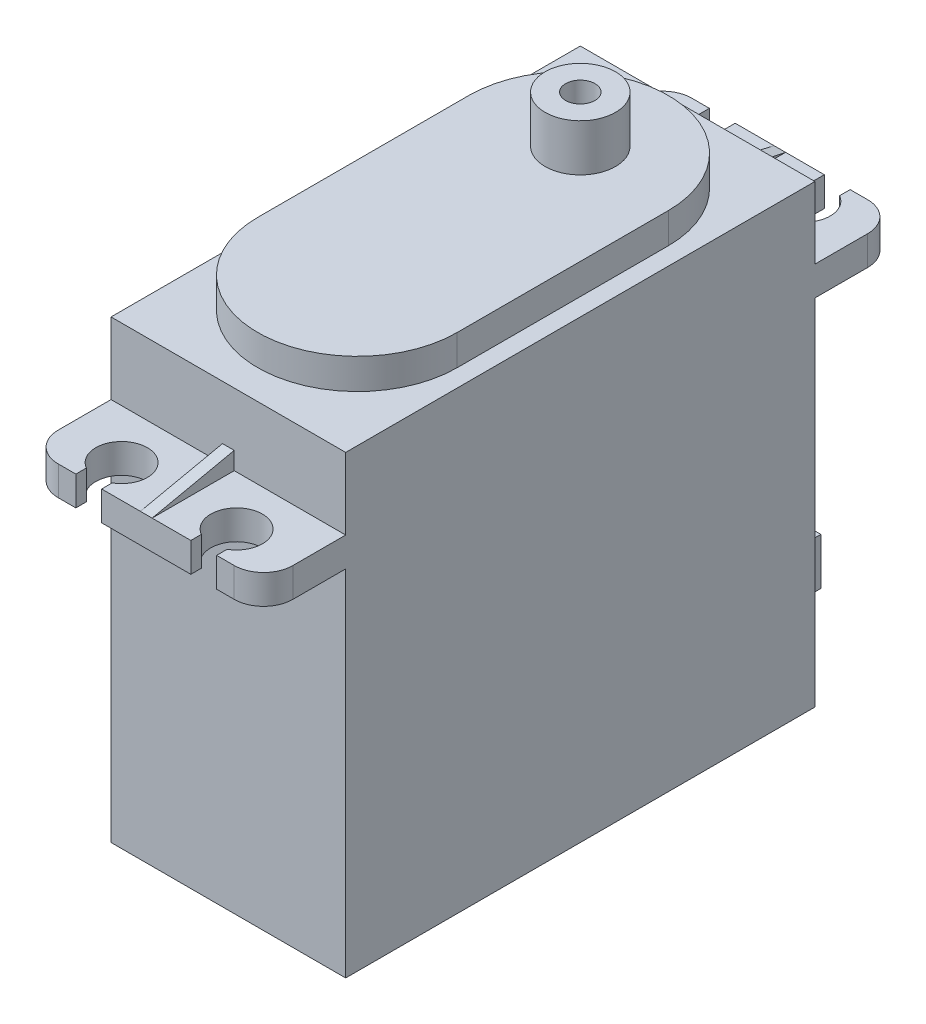
SolidWorks part; units mm, degrees
ref_plane "前视基准面" through (0, 0, 0) normal (0, 0, 1) x (1, 0, 0)
ref_plane "上视基准面" through (0, 0, 0) normal (0, 1, 0) x (1, 0, 0)
ref_plane "右视基准面" through (0, 0, 0) normal (1, 0, 0) x (0, 0, -1)
other "Configuration Table"
sketch "草图1" plane through (0, 0, 0) normal (0, 1, 0) x (1, 0, 0)
  line L1 (-10, 20) -> (10, 20)
  line L2 (-10, 20) -> (-10, -20)
  line L3 (-10, -20) -> (10, -20)
  line L4 (10, 20) -> (10, -20)
  line L5 (-10, 20) -> (10, -20) construction
  line L6 (-10, -20) -> (10, 20) construction
  point P0 (0, 0)
  dimension "D1" = 40
  dimension "D2" = 20
extrude "凸台-拉伸1" add sketch "草图1" along normal blind 38.8
sketch "草图2" plane through (0, 0, 0) normal (0, 1, 0) x (1, 0, 0)
  line L0 (-10, 20) -> (-10, -20) construction
  line L1 (-7.5, -27) -> (-6, -27)
  line L2 (-10, -24.5) -> (-10, 24.5)
  line L3 (-7.5, 27) -> (-6, 27)
  line L4 (10, -24.5) -> (10, 24.5)
  line L5 (-10, -27) -> (10, 27) construction
  line L6 (-10, 27) -> (10, -27) construction
  line L7 (0, 42.6693) -> (0, -40.1574) construction
  line L8 (-24.1871, 0) -> (28.7742, 0) construction
  line L9 (-4.9, 28.4699) -> (-4.9, 24.2) construction
  line L10 (-6, 27) -> (-6, 26.1053)
  line L11 (-3.8, 27) -> (-3.8, 26.1053)
  line L12 (-3.8, 27) -> (3.8, 27)
  line L13 (3.8, 27) -> (3.8, 26.1053)
  line L14 (6, 27) -> (6, 26.1053)
  line L15 (6, 27) -> (7.5, 27)
  line L16 (6, -27) -> (6, -26.1053)
  line L17 (3.8, -27) -> (3.8, -26.1053)
  line L18 (-3.8, -27) -> (-3.8, -26.1053)
  line L19 (-6, -27) -> (-6, -26.1053)
  line L20 (-3.8, -27) -> (3.8, -27)
  line L21 (6, -27) -> (7.5, -27)
  arc A0 (-6, 26.1053) -> (-3.8, 26.1053) centre (-4.9, 24.2) ccw
  arc A4 (6, 26.1053) -> (3.8, 26.1053) centre (4.9, 24.2) cw
  arc A5 (6, -26.1053) -> (3.8, -26.1053) centre (4.9, -24.2) ccw
  arc A6 (-6, -26.1053) -> (-3.8, -26.1053) centre (-4.9, -24.2) cw
  arc A7 (-10, 24.5) -> (-7.5, 27) centre (-7.5, 24.5) cw
  arc A8 (10, 24.5) -> (7.5, 27) centre (7.5, 24.5) ccw
  arc A9 (7.5, -27) -> (10, -24.5) centre (7.5, -24.5) ccw
  arc A10 (-10, -24.5) -> (-7.5, -27) centre (-7.5, -24.5) ccw
  point P0 (0, 0)
  dimension "D2" = 4.4
  dimension "D6" = 2.5
  dimension "D1" = 54
  dimension "D3" = 2.2
  dimension "D4" = 9.8
  dimension "D5" = 48.4
extrude "凸台-拉伸2" add sketch "草图2" against normal blind 2.5 from offset 32.7
sketch "草图3" plane through (0, 0, 0) normal (1, 0, 0) x (0, 0, -1)
  line L0 (0, 55.7992) -> (0, 0) construction
  line L1 (-20, 32.7) -> (-27, 32.7)
  line L2 (-27, 32.7) -> (-20, 34.2)
  line L3 (-20, 38.8) -> (-20, 32.7) construction
  line L4 (-20, 34.2) -> (-20, 32.7)
  line L5 (20, 34.2) -> (20, 32.7)
  line L6 (27, 32.7) -> (20, 34.2)
  line L7 (20, 32.7) -> (27, 32.7)
  dimension "D1" = 1.5
extrude "凸台-拉伸3" add sketch "草图3" along normal mid plane 1
sketch "草图4" plane through (0, 0, 0) normal (0, 1, 0) x (1, 0, 0)
  line L0 (-19.4568, 0) -> (19.4568, 0) construction
  line L2 (8.5, -9) -> (8.5, 9)
  line L4 (-8.5, -9) -> (-8.5, 9)
  line L5 (0, 0) -> (0, 33.0045) construction
  arc A0 (8.5, 9) -> (-8.5, 9) centre (0, 9) ccw
  arc A1 (8.5, -9) -> (-8.5, -9) centre (0, -9) cw
  point P0 (0, 0)
  point P12 (8.5, 0)
  point P13 (-8.5, 0)
  point P14 (0, 17.5)
  point P15 (0, -17.5)
  dimension "D2" = 35
  dimension "D1" = 17
  dimension "D3" = 18
  dimension "D4" = 18
extrude "凸台-拉伸4" add sketch "草图4" along normal blind 2.6 from surface at 38.8 starting at face at (0, 38.8, 0)
sketch "草图5" plane through (0, 0, 0) normal (0, 1, 0) x (1, 0, 0)
  line L0 (0, 30.7966) -> (0, 0) construction
  circle A0 centre (0, 10) radius 3
  circle A1 centre (0, 10) radius 1.25
  dimension "D2" = 6
  dimension "D3" = 2.5
  dimension "D1" = 10
extrude "凸台-拉伸5" add sketch "草图5" along normal blind 4 from surface at 41.4 separate body starting at face at (0, 41.4, 0)
sketch "草图6" plane through (0, 0, 0) normal (0, 0, 1) x (1, 0, 0)
  line L0 (0, 18.3818) -> (0, 0) construction
  line L1 (-10, 0) -> (10, 0) construction
  line L2 (-3.5, 6) -> (3.5, 6)
  line L3 (-3.5, 6) -> (-3.5, 2)
  line L4 (-3.5, 2) -> (3.5, 2)
  line L5 (3.5, 6) -> (3.5, 2)
  line L6 (-3.5, 6) -> (3.5, 2) construction
  line L7 (-3.5, 2) -> (3.5, 6) construction
  point P3 (0, 4)
  dimension "D1" = 2
  dimension "D2" = 4
  dimension "D3" = 7
extrude "凸台-拉伸6" add sketch "草图6" against normal blind 7 from surface at -20 separate body starting at face at (0, 15.1, -20)
